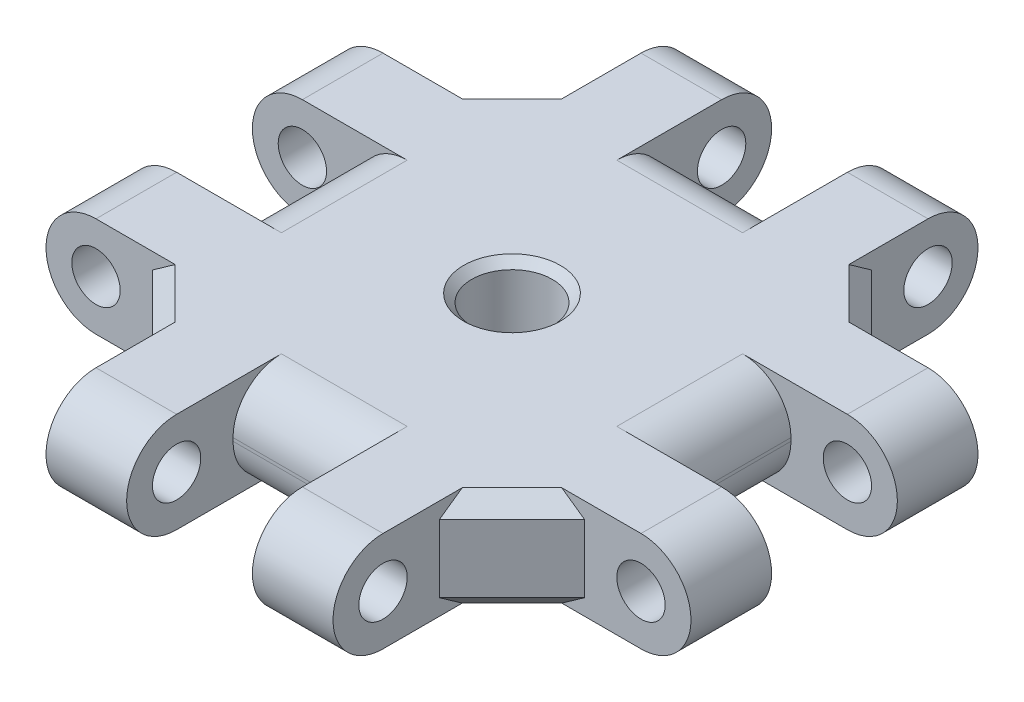
SolidWorks part; units mm, degrees
ref_plane "Front Plane" through (0, 0, 0) normal (0, 0, 1) x (1, 0, 0)
ref_plane "Top Plane" through (0, 0, 0) normal (0, 1, 0) x (1, 0, 0)
ref_plane "Right Plane" through (0, 0, 0) normal (1, 0, 0) x (0, 0, -1)
sketch "Sketch1" plane through (0, 0, 0) normal (0, 1, 0) x (1, 0, 0)
  line L0 (-8.9, -13.4) -> (-8.9, -20.4)
  line L1 (-13.4, -13.4) -> (13.4, -13.4) construction
  line L2 (-13.4, -13.4) -> (-13.4, 13.4) construction
  line L3 (-13.4, 13.4) -> (13.4, 13.4) construction
  line L4 (13.4, -13.4) -> (13.4, 13.4) construction
  line L5 (-13.4, -13.4) -> (13.4, 13.4) construction
  line L6 (-13.4, 13.4) -> (13.4, -13.4) construction
  line L7 (-8.9, -20.4) -> (-3.9, -20.4)
  line L8 (-3.9, -20.4) -> (-3.9, -13.4)
  line L9 (-3.9, -13.4) -> (3.9, -13.4)
  line L10 (3.9, -13.4) -> (3.9, -20.4)
  line L11 (3.9, -20.4) -> (8.9, -20.4)
  line L12 (8.9, -20.4) -> (8.9, -13.4)
  line L13 (-8.9, -13.4) -> (-13.4, -13.4) construction
  line L14 (-13.4, 8.9) -> (-20.4, 8.9)
  line L15 (-20.4, 8.9) -> (-20.4, 3.9)
  line L16 (-20.4, 3.9) -> (-13.4, 3.9)
  line L17 (-13.4, 3.9) -> (-13.4, -3.9)
  line L18 (-13.4, -3.9) -> (-20.4, -3.9)
  line L19 (-20.4, -3.9) -> (-20.4, -8.9)
  line L20 (-20.4, -8.9) -> (-13.4, -8.9)
  line L21 (8.9, 13.4) -> (8.9, 20.4)
  line L22 (8.9, 20.4) -> (3.9, 20.4)
  line L23 (3.9, 20.4) -> (3.9, 13.4)
  line L24 (3.9, 13.4) -> (-3.9, 13.4)
  line L25 (-3.9, 13.4) -> (-3.9, 20.4)
  line L26 (-3.9, 20.4) -> (-8.9, 20.4)
  line L27 (-8.9, 20.4) -> (-8.9, 13.4)
  line L28 (13.4, -8.9) -> (20.4, -8.9)
  line L29 (20.4, -8.9) -> (20.4, -3.9)
  line L30 (20.4, -3.9) -> (13.4, -3.9)
  line L31 (13.4, -3.9) -> (13.4, 3.9)
  line L32 (13.4, 3.9) -> (20.4, 3.9)
  line L33 (20.4, 3.9) -> (20.4, 8.9)
  line L34 (20.4, 8.9) -> (13.4, 8.9)
  line L35 (-13.4, 8.9) -> (-8.9, 13.4)
  line L36 (8.9, 13.4) -> (13.4, 8.9)
  line L37 (13.4, -8.9) -> (8.9, -13.4)
  line L38 (-8.9, -13.4) -> (-13.4, -8.9)
  circle A0 centre (0, 0) radius 2.5
  point P0 (0, 0)
  point P17 (0, 0)
  point P26 (0, 0)
  point P35 (0, 0)
  point P44 (0, 0)
  dimension "D2" = 5
  dimension "D3" = 5
  dimension "D4" = 7.8
  dimension "D5" = 7
  dimension "D6" = 7
  dimension "D7" = 4.5
  dimension "D8" = 4
extrude "Boss-Extrude1" add sketch "Sketch1" along normal mid plane 6.2
sketch "Sketch2" plane through (-8.9, 0, 0) normal (-1, 0, 0) x (0, 0, 1)
  line L0 (13.4, 3.1) -> (20.4, -3.1) construction
  line L1 (20.4, 3.1) -> (13.4, -3.1) construction
  line L2 (13.4, 3.1) -> (20.4, 3.1) construction
  line L3 (13.4, -3.1) -> (20.4, -3.1) construction
  line L4 (16.9, 3.1) -> (20.4, 3.1)
  line L5 (20.4, 3.1) -> (20.4, -3.1)
  line L6 (20.4, -3.1) -> (16.9, -3.1)
  circle A0 centre (16.9, 0) radius 1.5
  arc A1 (16.9, 3.1) -> (16.9, -3.1) centre (16.9, 0) cw
  dimension "D1" = 3
extrude "Cut-Extrude1" cut sketch "Sketch2" against normal through all both and the other way through all
pattern_circular "CirPattern1" count 4 every 90 about axis through (0, 3.1, 0) along (0, 1, 0) of "Cut-Extrude1"
fillet "Fillet1" radius 3 8 edges at (0, -3.1, 13.4) (-13.4, -3.1, 0) (13.4, -3.1, 0) (0, -3.1, -13.4) (-13.4, 3.1, 0) (0, 3.1, -13.4) (13.4, 3.1, 0) (0, 3.1, 13.4)
chamfer "Chamfer1" distance 1 angle 45 8 edges at (11.15, -3.1, 11.15) (11.15, 3.1, 11.15) (11.15, -3.1, -11.15) (11.15, 3.1, -11.15) (-11.15, -3.1, -11.15) (-11.15, 3.1, -11.15) (-11.15, -3.1, 11.15) (-11.15, 3.1, 11.15)
chamfer "Chamfer3" distance 0.5 angle 45 2 edges at (0, -3.1, 2.5) (0, 3.1, 2.5)
